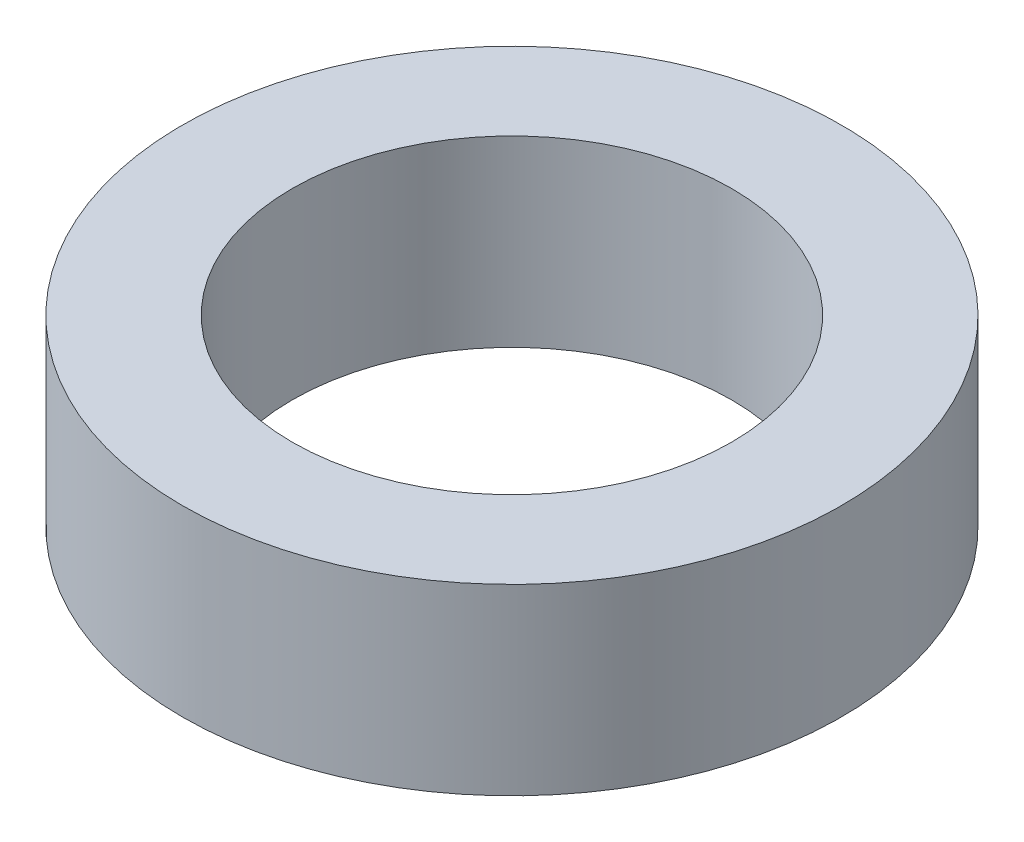
SolidWorks part; units mm, degrees
ref_plane "Front Plane" through (0, 0, 0) normal (0, 0, 1) x (1, 0, 0)
ref_plane "Top Plane" through (0, 0, 0) normal (0, 1, 0) x (1, 0, 0)
ref_plane "Right Plane" through (0, 0, 0) normal (1, 0, 0) x (0, 0, -1)
sketch "Sketch1" plane through (0, 0, 0) normal (0, 1, 0) x (1, 0, 0)
  circle A0 centre (0, 0) radius 12
  circle A1 centre (0, 0) radius 18
extrude "Boss-Extrude1" add sketch "Sketch1" along normal blind 10
